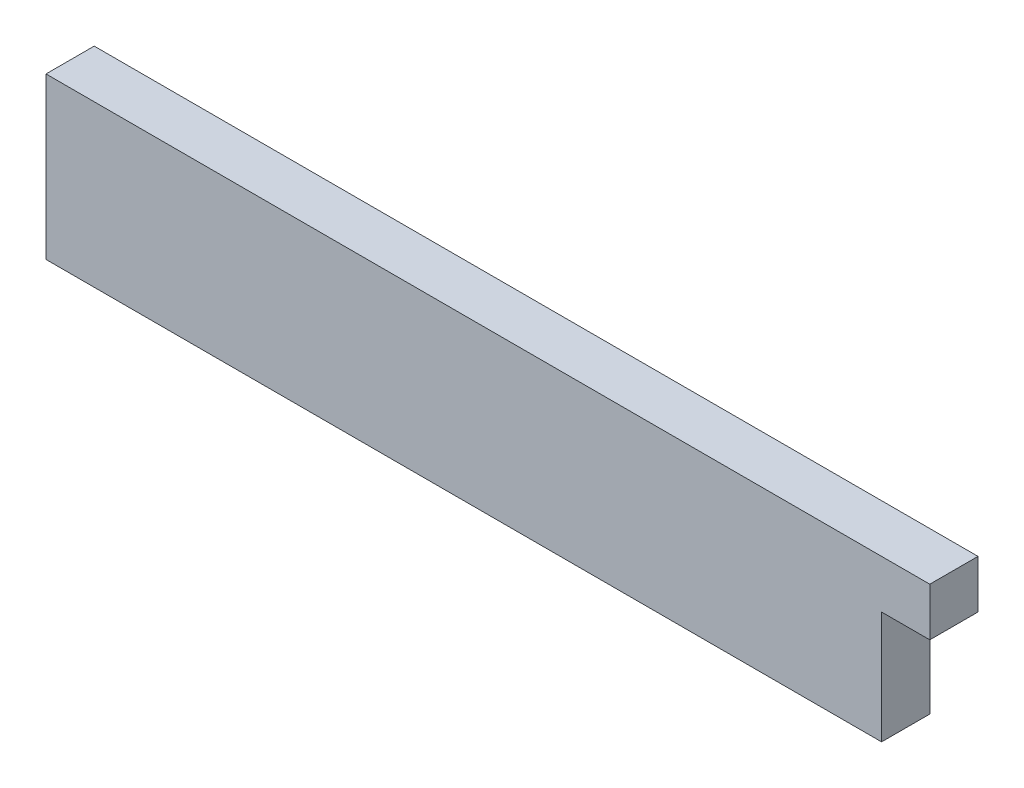
SolidWorks part; units mm, degrees
ref_plane "Front Plane" through (0, 0, 0) normal (0, 0, 1) x (1, 0, 0)
ref_plane "Top Plane" through (0, 0, 0) normal (0, 1, 0) x (1, 0, 0)
ref_plane "Right Plane" through (0, 0, 0) normal (1, 0, 0) x (0, 0, -1)
sketch "Sketch1" plane through (0, 0, 0) normal (0, 0, 1) x (1, 0, 0)
  line L0 (42, 10) -> (55, 10)
  line L1 (0, 0) -> (52, 0)
  line L2 (0, 0) -> (0, 10)
  line L3 (0, 10) -> (42, 10)
  line L4 (52, 0) -> (52, 7)
  line L5 (55, 10) -> (55, 7)
  line L6 (55, 7) -> (52, 7)
  dimension "D1" = 52
  dimension "D2" = 10
  dimension "D3" = 3
  dimension "D4" = 3
extrude "Boss-Extrude1" add sketch "Sketch1" along normal blind 3
